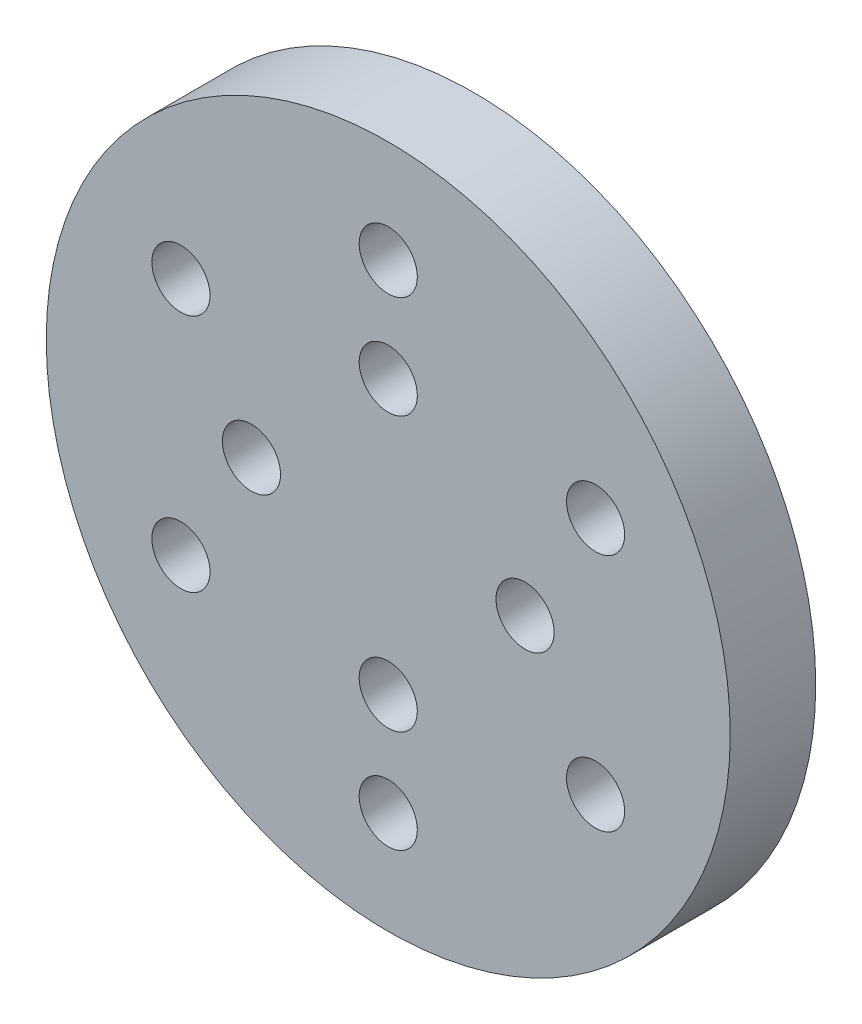
SolidWorks part; units mm, degrees
ref_plane "前视基准面" through (0, 0, 0) normal (0, 0, 1) x (1, 0, 0)
ref_plane "上视基准面" through (0, 0, 0) normal (0, 1, 0) x (1, 0, 0)
ref_plane "右视基准面" through (0, 0, 0) normal (1, 0, 0) x (0, 0, -1)
other "Configuration Table"
sketch "草图1" plane through (0, 0, 0) normal (0, 0, 1) x (1, 0, 0)
  line L0 (0, 0) -> (0, 8) construction
  circle A0 centre (0, 0) radius 20
  circle A1 centre (0, 8) radius 1.7
  circle A2 centre (8, 0) radius 1.7
  circle A3 centre (0, -8) radius 1.7
  circle A4 centre (-8, 0) radius 1.7
  point P14 (0, 0)
  dimension "D1" = 40
  dimension "D2" = 3.4
  dimension "D3" = 8
  dimension "D4" = 4
extrude "凸台-拉伸1" add sketch "草图1" along normal blind 5
sketch "草图2" plane through (0, 0, 5) normal (0, 0, 1) x (1, 0, 0)
  line L0 (0, 0) -> (0, 14) construction
  circle A0 centre (0, 14) radius 1.7
  circle A1 centre (12.1244, 7) radius 1.7
  circle A2 centre (12.1244, -7) radius 1.7
  circle A3 centre (0, -14) radius 1.7
  circle A4 centre (-12.1244, -7) radius 1.7
  circle A5 centre (-12.1244, 7) radius 1.7
  point P16 (0, 0)
  dimension "D2" = 3.4
  dimension "D1" = 14
  dimension "D3" = 6
extrude "切除-拉伸1" cut sketch "草图2" against normal blind 5
